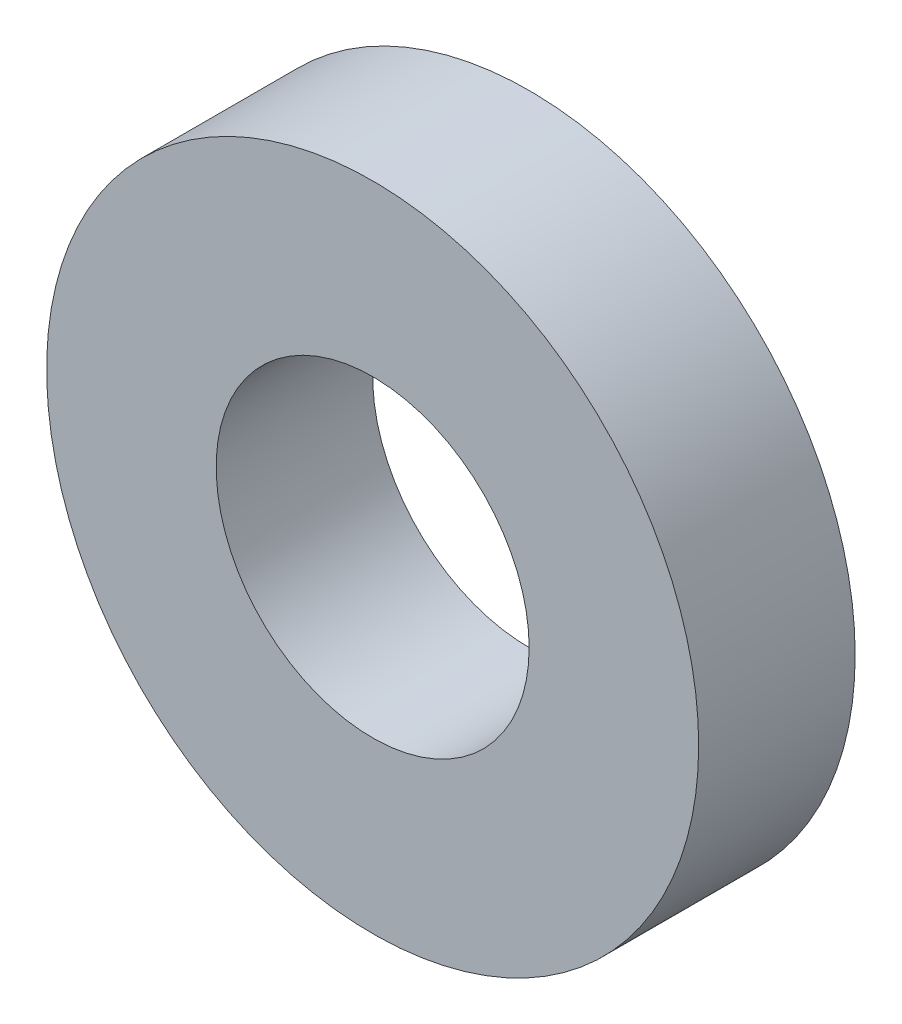
SolidWorks part; units mm, degrees
ref_plane "前视基准面" through (0, 0, 0) normal (0, 0, 1) x (1, 0, 0)
ref_plane "上视基准面" through (0, 0, 0) normal (0, 1, 0) x (1, 0, 0)
ref_plane "右视基准面" through (0, 0, 0) normal (1, 0, 0) x (0, 0, -1)
sketch "草图1" plane through (0, 0, 0) normal (0, 0, 1) x (1, 0, 0)
  circle A0 centre (0, 0) radius 12.5
  dimension "D1" = 25
extrude "凸台-拉伸1" add sketch "草图1" along normal blind 6
sketch "草图2" plane through (0, 0, 6) normal (0, 0, 1) x (1, 0, 0)
  circle A0 centre (0, 0) radius 6
extrude "切除-拉伸1" cut sketch "草图2" against normal through all both and the other way through all contours A0
